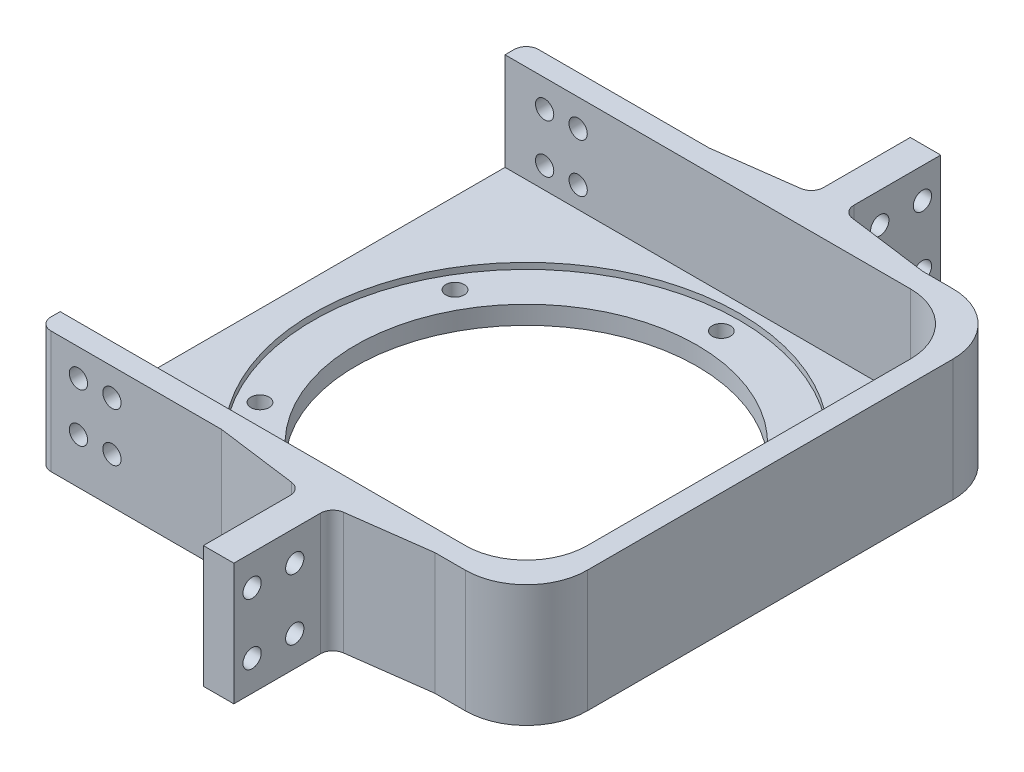
SolidWorks part; units mm, degrees
material "6061 合金"
ref_plane "前视基准面" through (0, 0, 0) normal (0, 0, 1) x (1, 0, 0)
ref_plane "上视基准面" through (0, 0, 0) normal (0, 1, 0) x (1, 0, 0)
ref_plane "右视基准面" through (0, 0, 0) normal (1, 0, 0) x (0, 0, -1)
sketch "草图1" plane through (0, 0, 0) normal (0, 1, 0) x (1, 0, 0)
  line L1 (-40, 40) -> (40, 40)
  line L2 (-40, 40) -> (-40, -40)
  line L3 (-40, -40) -> (40, -40)
  line L4 (40, 40) -> (40, -40)
  line L5 (0, 32) -> (-27.7128, 16) construction
  line L6 (-27.7128, 16) -> (-27.7128, -16) construction
  line L7 (-27.7128, -16) -> (0, -32) construction
  line L8 (0, -32) -> (27.7128, -16) construction
  line L9 (27.7128, -16) -> (27.7128, 16) construction
  line L10 (27.7128, 16) -> (0, 32) construction
  circle A0 centre (0, 0) radius 28
  circle A1 centre (0, 0) radius 32 construction
  circle A2 centre (0, 32) radius 1.5
  circle A3 centre (27.7128, 16) radius 1.5
  circle A4 centre (27.7128, -16) radius 1.5
  circle A5 centre (0, -32) radius 1.5
  circle A6 centre (-27.7128, -16) radius 1.5
  circle A7 centre (-27.7128, 16) radius 1.5
  point P7 (0, 40)
  point P8 (-40, 0)
  dimension "D1" = 64
  dimension "D2" = 3
  dimension "D3" = 56
  dimension "D4" = 80
extrude "凸台-拉伸1" add sketch "草图1" along normal blind 4
sketch "草图2" plane through (0, 4, 0) normal (0, 1, 0) x (1, 0, 0)
  line L2 (40, 40) -> (-40, 40) construction
  line L3 (40, 40) -> (-40, 40)
  line L4 (40, -40) -> (40, 40) construction
  line L5 (40, -40) -> (40, 40)
  line L6 (-40, -40) -> (40, -40) construction
  line L7 (-40, -40) -> (40, -40)
  line L8 (-40, 40) -> (-40, 36.5)
  line L9 (-36.5, 36.5) -> (36.5, 36.5)
  line L10 (-36.5, 36.5) -> (-36.5, -36.5) construction
  line L11 (-36.5, -36.5) -> (36.5, -36.5)
  line L12 (36.5, 36.5) -> (36.5, -36.5)
  line L13 (-40, 40) -> (-40, -40) construction
  line L14 (-40, 36.5) -> (-36.5, 36.5)
  line L15 (-40, -40) -> (-40, -36.5)
  line L16 (-40, -36.5) -> (-36.5, -36.5)
  point P8 (0, 36.5)
  point P10 (-36.5, 0)
  dimension "D1" = 3.5
extrude "凸台-拉伸2" add sketch "草图2" along normal blind 16
sketch "草图9" plane through (0, 20, 0) normal (0, 1, 0) x (1, 0, 0)
  line L15 (-40, 0) -> (40, 0) construction
  line L27 (40, -40) -> (40, 40) construction
  line L28 (-10, -40) -> (-10, -58)
  line L29 (-40, -40) -> (40, -40) construction
  line L30 (-10, -58) -> (-5, -58)
  line L31 (-5, -58) -> (-5, -40)
  line L32 (-5, -40) -> (-10, -40)
  line L33 (5, -40) -> (5, -58)
  line L34 (5, -58) -> (10, -58)
  line L35 (10, -58) -> (10, -40)
  line L36 (10, -40) -> (5, -40)
  line L37 (-5, -49) -> (5, -49) construction
  line L38 (-5, 49) -> (5, 49) construction
  line L39 (10, 40) -> (5, 40)
  line L40 (10, 58) -> (10, 40)
  line L41 (5, 58) -> (10, 58)
  line L42 (5, 40) -> (5, 58)
  line L43 (-5, 40) -> (-10, 40)
  line L44 (-5, 58) -> (-5, 40)
  line L45 (-10, 58) -> (-5, 58)
  line L46 (-10, 40) -> (-10, 58)
  point P19 (0, -49)
  dimension "D1" = 5
  dimension "D2" = 18
  dimension "D3" = 20
extrude "凸台-拉伸6" add sketch "草图9" against normal up to surface (20 mm away) up to face at (0, 0, 0)
sketch "草图10" plane through (0, 20, 0) normal (0, 1, 0) x (1, 0, 0)
  line L0 (-10, -42) -> (-25, -40)
  line L1 (-10, -40) -> (-10, -58) construction
  line L2 (-40, -40) -> (-10, -40) construction
  line L3 (-25, -40) -> (-10, -40)
  line L4 (-10, -40) -> (-10, -42)
  line L5 (0, 40) -> (0, -40) construction
  line L6 (5, 40) -> (-5, 40) construction
  line L7 (-5, -40) -> (5, -40) construction
  line L8 (-40, 0) -> (40, 0) construction
  line L10 (40, -40) -> (40, 40) construction
  line L11 (10, -40) -> (10, -42)
  line L12 (25, -40) -> (10, -40)
  line L13 (10, -42) -> (25, -40)
  line L14 (10, 42) -> (25, 40)
  line L15 (25, 40) -> (10, 40)
  line L16 (10, 40) -> (10, 42)
  line L17 (-10, 40) -> (-10, 42)
  line L18 (-25, 40) -> (-10, 40)
  line L19 (-10, 42) -> (-25, 40)
  line L20 (-5, 40) -> (-5, 58) construction
  line L21 (-5, 42) -> (5, 42)
  line L22 (-5, 42) -> (-5, 40)
  line L23 (-5, 40) -> (5, 40)
  line L24 (5, 42) -> (5, 40)
  line L25 (5, -40) -> (5, -58) construction
  line L26 (-5, -40) -> (5, -40)
  line L27 (-5, -40) -> (-5, -42)
  line L28 (-5, -42) -> (5, -42)
  line L29 (5, -40) -> (5, -42)
  dimension "D1" = 2
  dimension "D2" = 15
extrude "凸台-拉伸7" [suppressed] add sketch "草图10" against normal up to surface (20 mm away)
sketch "草图11" plane through (-10, 0, 0) normal (-1, 0, 0) x (0, 0, 1)
  line L0 (48, 15) -> (48, 5) construction
  line L1 (48, 5) -> (55, 5) construction
  line L2 (55, 5) -> (55, 15) construction
  line L3 (55, 15) -> (48, 15) construction
  line L4 (58, 0) -> (58, 20) construction
  line L5 (0, 0) -> (0, 20) construction
  line L7 (-55, 15) -> (-48, 15) construction
  line L8 (-55, 5) -> (-55, 15) construction
  line L9 (-48, 5) -> (-55, 5) construction
  line L10 (-48, 15) -> (-48, 5) construction
  circle A0 centre (55, 15) radius 1.5
  circle A1 centre (55, 5) radius 1.5
  circle A2 centre (48, 5) radius 1.5
  circle A3 centre (48, 15) radius 1.5
  circle A4 centre (-48, 15) radius 1.5
  circle A5 centre (-48, 5) radius 1.5
  circle A6 centre (-55, 5) radius 1.5
  circle A7 centre (-55, 15) radius 1.5
  point P10 (58, 10)
  point P11 (55, 10)
  dimension "D3" = 3
  dimension "D1" = 10
  dimension "D2" = 7
  dimension "D4" = 3
extrude "切除-拉伸2" cut sketch "草图11" against normal through all
sketch "草图12" plane through (0, 4, 0) normal (0, 1, 0) x (1, 0, 0)
  circle A12 centre (0, 0) radius 28 construction
  circle A13 centre (0, 0) radius 28
  circle A14 centre (0, 0) radius 35
  dimension "D1" = 70
extrude "切除-拉伸3" cut sketch "草图12" against normal blind 1
fillet "圆角6" radius 10 4 edges at (36.5, 12, -36.5) (36.5, 12, 36.5) (40, 10, -40) (40, 10, 40)
fillet "圆角7" [suppressed] radius 2.5
sketch "草图13" plane through (0, 0, 58) normal (0, 0, 1) x (1, 0, 0)
  line L0 (-33.5, 7.5) -> (-28, 7.5) construction
  line L1 (-40, 0) -> (-10, 0) construction
  line L3 (-33.5, 7.5) -> (-33.5, 15.5) construction
  line L4 (-33.5, 15.5) -> (-28, 15.5) construction
  line L5 (-28, 15.5) -> (-28, 7.5) construction
  circle A0 centre (-33.5, 7.5) radius 1.5
  circle A1 centre (-28, 7.5) radius 1.5
  circle A3 centre (-33.5, 15.5) radius 1.5
  circle A4 centre (-28, 15.5) radius 1.5
  dimension "D2" = 3
  dimension "D3" = 7.5
  dimension "D1" = 5.5
  dimension "D4" = 28
  dimension "D5" = 8
extrude "切除-拉伸4" cut sketch "草图13" against normal through all
fillet "圆角8" radius 2 2 edges at (-40, 10, -40) (-40, 10, 40)
sketch "草图15" plane through (0, 20, 0) normal (0, 1, 0) x (1, 0, 0)
  line L1 (-5, -58) -> (-10, -58)
  line L2 (-5, -58) -> (-5, -40)
  line L3 (-5, -40) -> (-10, -40)
  line L4 (-10, -58) -> (-10, -40)
  line L5 (-10, 58) -> (-5, 58)
  line L6 (-10, 58) -> (-10, 40)
  line L7 (-10, 40) -> (-5, 40)
  line L8 (-5, 58) -> (-5, 40)
extrude "切除-拉伸6" cut sketch "草图15" against normal through all
sketch "草图16" plane through (0, 20, 0) normal (0, 1, 0) x (1, 0, 0)
  line L0 (0, 0) -> (-15.3868, 0) construction
  line L1 (10, -42) -> (25, -40)
  line L2 (10, -58) -> (10, -40) construction
  line L3 (10, -40) -> (30, -40) construction
  line L4 (10, -42) -> (10, -40)
  line L5 (10, -40) -> (25, -40)
  line L6 (7.5, -58) -> (7.5, -38.3838) construction
  line L7 (5, -58) -> (10, -58) construction
  line L8 (5, -42) -> (5, -40)
  line L9 (5, -42) -> (-10, -40)
  line L10 (5, -40) -> (-10, -40)
  line L11 (10, 42) -> (10, 40)
  line L12 (10, 42) -> (25, 40)
  line L13 (10, 40) -> (25, 40)
  line L14 (5, 42) -> (-10, 40)
  line L15 (5, 40) -> (-10, 40)
  line L16 (5, 42) -> (5, 40)
  dimension "D1" = 2
  dimension "D2" = 15
extrude "凸台-拉伸8" add sketch "草图16" against normal blind 20
fillet "圆角9" radius 2 4 edges at (5, 10, -42) (10, 10, -42) (10, 10, 42) (5, 10, 42)
sketch "草图17" plane through (0, 0, 0) normal (0, 0, 1) x (1, 0, 0)
  line L0 (19.5, 15.5) -> (27.5, 15.5) construction
  line L1 (27.5, 15.5) -> (27.5, 7.5) construction
  line L2 (27.5, 7.5) -> (19.5, 7.5) construction
  line L3 (19.5, 7.5) -> (19.5, 15.5) construction
  line L4 (36.5, 20) -> (36.5, 4) construction
  circle A0 centre (19.5, 15.5) radius 1.5
  circle A1 centre (27.5, 15.5) radius 1.5
  circle A2 centre (19.5, 7.5) radius 1.5
  circle A3 centre (27.5, 7.5) radius 1.5
  circle A4 centre (-28, 15.5) radius 1.5 construction
  circle A5 centre (-28, 15.5) radius 1.5 construction
  circle A6 centre (-28, 7.5) radius 1.5 construction
  circle A7 centre (-28, 7.5) radius 1.5 construction
  dimension "D1" = 3
  dimension "D2" = 8
  dimension "D3" = 9
  dimension "D4" = 8
extrude "切除-拉伸7" [suppressed] cut sketch "草图17" against normal mid plane 100
